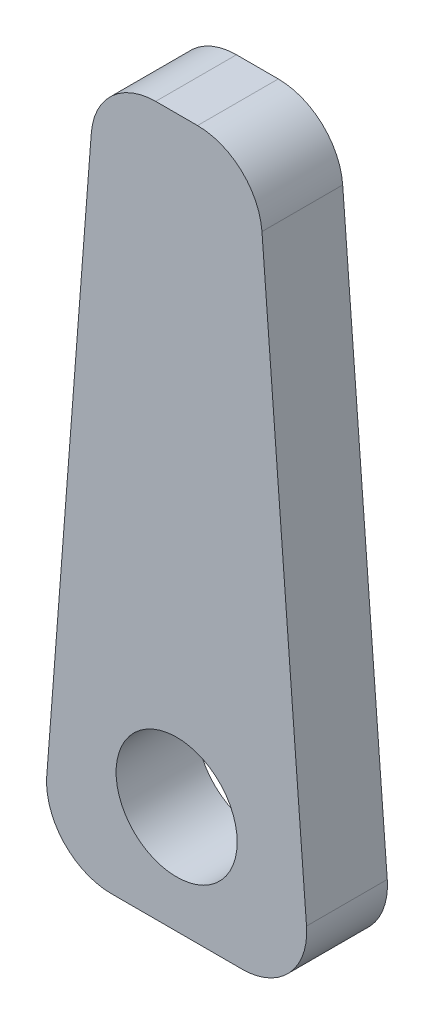
SolidWorks part; units mm, degrees
ref_plane "Front Plane" through (0, 0, 0) normal (0, 0, 1) x (1, 0, 0)
ref_plane "Top Plane" through (0, 0, 0) normal (0, 1, 0) x (1, 0, 0)
ref_plane "Right Plane" through (0, 0, 0) normal (1, 0, 0) x (0, 0, -1)
sketch "Sketch1" plane through (0, 0, 0) normal (0, 0, 1) x (1, 0, 0)
  line L3 (-0.8229, 165.1) -> (0.8229, 165.1)
  line L4 (3.3554, 162.7548) -> (5.1073, 139.9795)
  line L9 (-2.5748, 137.2447) -> (2.5748, 137.2447)
  line L10 (-5.1073, 139.9795) -> (-3.3554, 162.7548)
  line L11 (0, 137.2447) -> (0, 165.1)
  circle A0 centre (0, 141.478) radius 2.3812
  arc A1 (5.1073, 139.9795) -> (2.5748, 137.2447) centre (2.5748, 139.7847) cw
  arc A2 (-5.1073, 139.9795) -> (-2.5748, 137.2447) centre (-2.5748, 139.7847) ccw
  arc A3 (0.8229, 165.1) -> (3.3554, 162.7548) centre (0.8229, 162.56) cw
  arc A4 (-3.3554, 162.7548) -> (-0.8229, 165.1) centre (-0.8229, 162.56) cw
  dimension "D1" = 4.7625
  dimension "D3" = 4.2333
  dimension "D4" = 2.54
extrude "Boss-Extrude1" add sketch "Sketch1" along normal blind 3.175 contours A0 L11 L3 L10 L9 | A0 L11 L9 L4 L3
